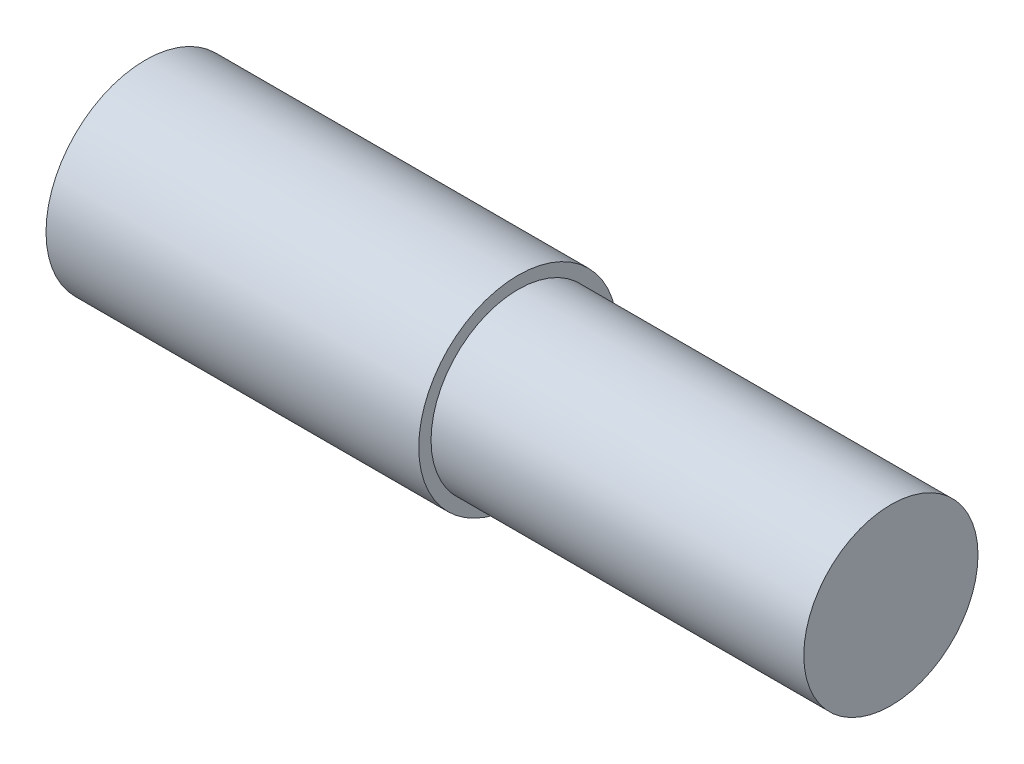
SolidWorks part; units mm, degrees
ref_plane "Front Plane" through (0, 0, 0) normal (0, 0, 1) x (1, 0, 0)
ref_plane "Top Plane" through (0, 0, 0) normal (0, 1, 0) x (1, 0, 0)
ref_plane "Right Plane" through (0, 0, 0) normal (1, 0, 0) x (0, 0, -1)
other "Bounding Box"
ref_plane "Default Plane" through (0, -4.6338, -3.2446) normal (0, 0.9848, -0.1736) x (1, 0, 0)
sketch "Sketch1" plane through (0, 0, 0) normal (1, 0, 0) x (0, 0, -1)
  circle A0 centre (0, 0) radius 4
extrude "Boss-Extrude1" add sketch "Sketch1" along normal blind 15 contours A0
sketch "Sketch2" plane through (0, 0, 0) normal (1, 0, 0) x (0, 0, -1)
  circle A0 centre (0, 0) radius 2.25
sketch "Sketch4" plane through (15, 0, 0) normal (1, 0, 0) x (0, 0, -1)
  circle A0 centre (0, 0) radius 3.5052
extrude "Boss-Extrude2" add sketch "Sketch4" along normal blind 15 contours A0
